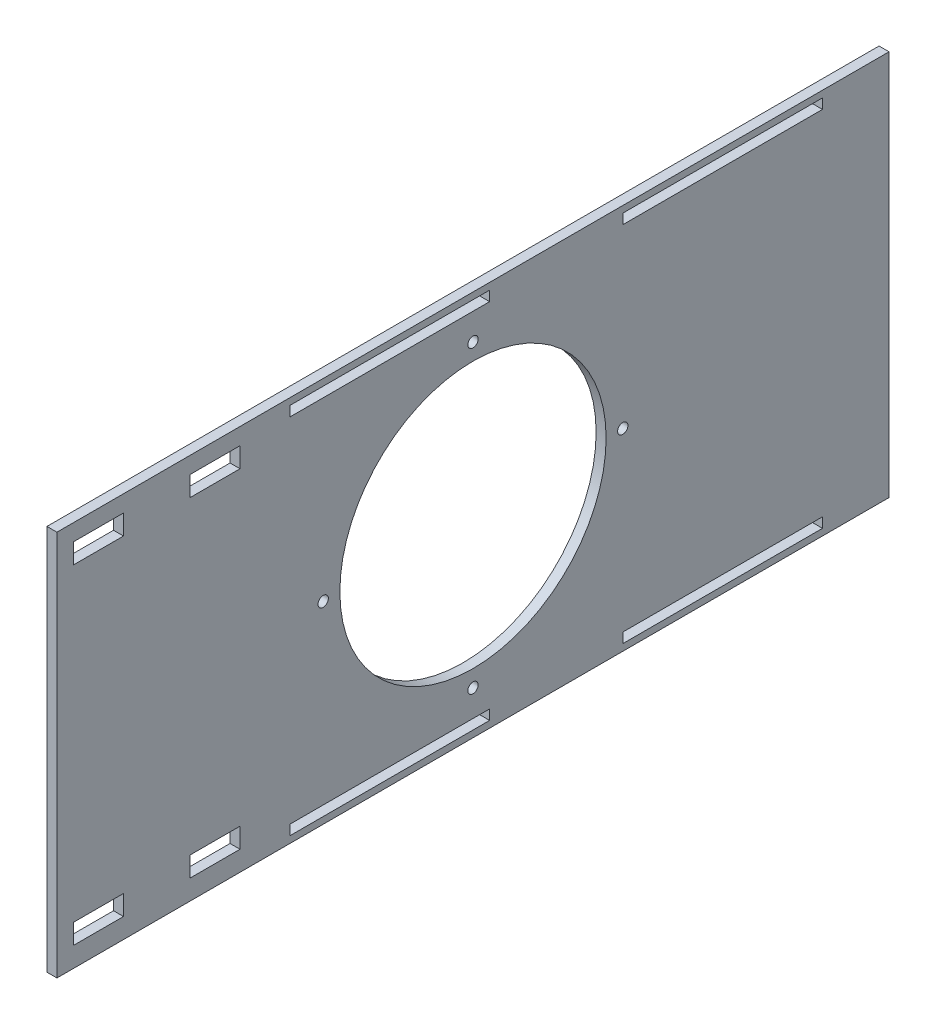
SolidWorks part; units mm, degrees
ref_plane "Plan de face" through (0, 0, 0) normal (0, 0, 1) x (1, 0, 0)
ref_plane "Plan de dessus" through (0, 0, 0) normal (0, 1, 0) x (1, 0, 0)
ref_plane "Plan de droite" through (0, 0, 0) normal (1, 0, 0) x (0, 0, -1)
sketch "Esquisse1" plane through (0, 0, 0) normal (1, 0, 0) x (0, 0, -1)
  line L2 (0, 0) -> (0, 116)
  line L5 (5, 111) -> (5, 105)
  line L6 (5, 105) -> (20, 105)
  line L7 (20, 105) -> (20, 111)
  line L8 (20, 111) -> (5, 111)
  line L9 (5, 12) -> (5, 6)
  line L10 (5, 6) -> (20, 6)
  line L11 (20, 6) -> (20, 12)
  line L12 (20, 12) -> (5, 12)
  line L25 (125, 98) -> (125, 103) construction
  line L26 (125, 18) -> (125, 13) construction
  line L27 (125, 116) -> (125, 0) construction
  line L28 (40, 111) -> (55, 111)
  line L29 (40, 111) -> (40, 105)
  line L30 (40, 105) -> (55, 105)
  line L31 (55, 111) -> (55, 105)
  line L32 (40, 12) -> (55, 12)
  line L33 (40, 12) -> (40, 6)
  line L34 (40, 6) -> (55, 6)
  line L35 (55, 12) -> (55, 6)
  line L48 (0, 116) -> (250, 116)
  line L49 (250, 0) -> (0, 0)
  line L50 (250, 116) -> (250, 0)
  line L51 (130, 113.9811) -> (70, 113.9811)
  line L52 (230, 114) -> (170, 114)
  line L53 (230, 114) -> (230, 111)
  line L54 (230, 111) -> (170, 111)
  line L55 (170, 114) -> (170, 111)
  line L56 (130, 113.9811) -> (130, 110.9811)
  line L57 (130, 110.9811) -> (70, 110.9811)
  line L58 (70, 113.9811) -> (70, 110.9811)
  line L59 (0, 58) -> (250, 58) construction
  line L60 (70, 2.0189) -> (70, 5.0189)
  line L61 (130, 5.0189) -> (70, 5.0189)
  line L62 (130, 2.0189) -> (130, 5.0189)
  line L63 (170, 2) -> (170, 5)
  line L64 (230, 5) -> (170, 5)
  line L65 (230, 2) -> (230, 5)
  line L66 (230, 2) -> (170, 2)
  line L67 (130, 2.0189) -> (70, 2.0189)
  circle A1 centre (125, 58) radius 40
  circle A2 centre (125, 103) radius 1.55
  circle A3 centre (125, 13) radius 1.55
  circle A4 centre (80, 58) radius 1.55
  circle A5 centre (170, 58) radius 1.55
  dimension "D23" = 3.1
  dimension "D24" = 3.1
  dimension "D25" = 3.1
  dimension "D26" = 3.1
  dimension "D2" = 6
  dimension "D4" = 5
  dimension "D5" = 5
  dimension "D6" = 6
  dimension "D7" = 116
  dimension "D8" = 15
  dimension "D9" = 3
  dimension "D10" = 15
  dimension "D11" = 60
  dimension "D12" = 20
  dimension "D13" = 6
  dimension "D14" = 0.0189
  dimension "D15" = 250
  dimension "D16" = 40
  dimension "D17" = 60
  dimension "D18" = 93
  dimension "D21" = 5
  dimension "D22" = 5
  dimension "D27" = 45
  dimension "D28" = 45
  dimension "D29" = 15
  dimension "D30" = 20
  dimension "D31" = 15
  dimension "D32" = 20
extrude "Boss.-Extru.1" add sketch "Esquisse1" along normal blind 3
